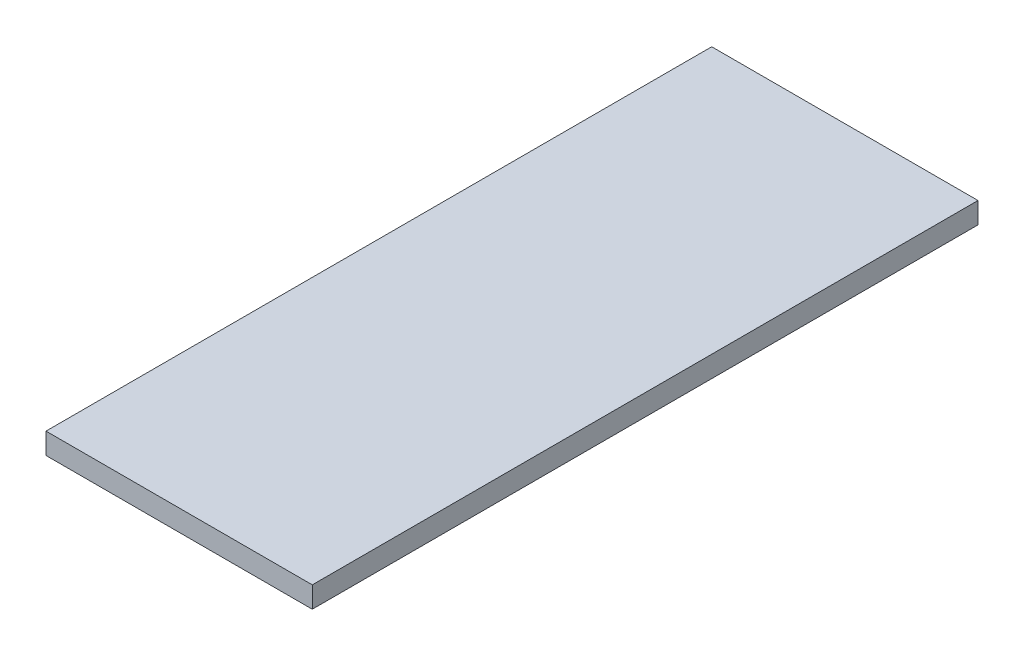
SolidWorks part; units mm, degrees
ref_plane "Alzado" through (0, 0, 0) normal (0, 0, 1) x (1, 0, 0)
ref_plane "Planta" through (0, 0, 0) normal (0, 1, 0) x (1, 0, 0)
ref_plane "Vista lateral" through (0, 0, 0) normal (1, 0, 0) x (0, 0, -1)
sketch "Croquis1" plane through (0, 0, 0) normal (0, 1, 0) x (1, 0, 0)
  line L1 (-160, 400) -> (160, 400)
  line L2 (-160, 400) -> (-160, -400)
  line L3 (-160, -400) -> (160, -400)
  line L4 (160, 400) -> (160, -400)
  line L5 (-160, 400) -> (160, -400) construction
  line L6 (-160, -400) -> (160, 400) construction
  point P0 (0, 0)
  dimension "D1" = 320
  dimension "D2" = 800
extrude "Saliente-Extruir1" add sketch "Croquis1" along normal blind 25.4
